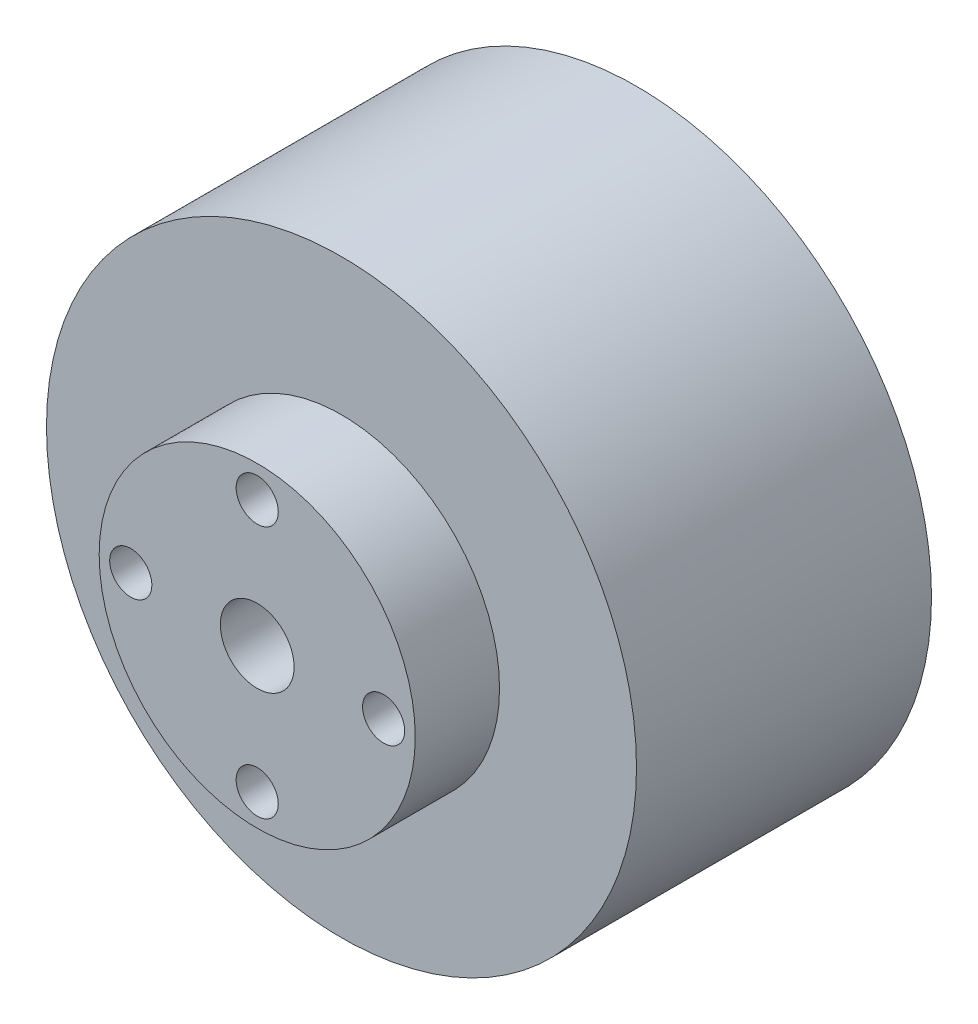
SolidWorks part; units mm, degrees
ref_plane "前视基准面" through (0, 0, 0) normal (0, 0, 1) x (1, 0, 0)
ref_plane "上视基准面" through (0, 0, 0) normal (0, 1, 0) x (1, 0, 0)
ref_plane "右视基准面" through (0, 0, 0) normal (1, 0, 0) x (0, 0, -1)
sketch "草图1" plane through (0, 0, 0) normal (0, 0, 1) x (1, 0, 0)
  circle A0 centre (0, 0) radius 14
  dimension "D1" = 28
extrude "凸台-拉伸1" add sketch "草图1" along normal blind 14
sketch "草图3" plane through (0, 0, 14) normal (0, 0, 1) x (1, 0, 0)
  circle A0 centre (0, 0) radius 7.5
  dimension "D1" = 15
extrude "凸台-拉伸3" add sketch "草图3" along normal blind 4
sketch "草图4" plane through (0, 0, 18) normal (0, 0, 1) x (1, 0, 0)
  circle A0 centre (0, 0) radius 1.75
  dimension "D1" = 3.5
extrude "切除-拉伸1" cut sketch "草图4" against normal through all
sketch "草图5" plane through (0, 0, 18) normal (0, 0, 1) x (1, 0, 0)
  line L0 (-17.4028, 0) -> (19.2585, 0) construction
  line L1 (0, 18.129) -> (0, -19.9613) construction
  circle A0 centre (0, -6) radius 1
  circle A1 centre (-6, 0) radius 1
  circle A2 centre (0, 6) radius 1
  circle A3 centre (6, 0) radius 1
  dimension "D1" = 2
  dimension "D2" = 6
  dimension "D3" = 6
  dimension "D4" = 6
  dimension "D5" = 6
extrude "切除-拉伸2" cut sketch "草图5" against normal blind 3 contours A3 | A1 | A0 | A2
sketch "草图6" plane through (0, 0, 0) normal (0, 0, 1) x (1, 0, 0)
  line L0 (24.9097, 0) -> (-28.6773, 0) construction
  line L1 (0, 19.7976) -> (0, -23.3744) construction
  circle A0 centre (0, 8) radius 1.5
  circle A1 centre (-8, 0) radius 1.5
  circle A2 centre (0, -8) radius 1.5
  circle A3 centre (8, 0) radius 1.5
  dimension "D1" = 3
  dimension "D2" = 8
  dimension "D3" = 8
  dimension "D4" = 8
  dimension "D5" = 8
extrude "切除-拉伸3" cut sketch "草图6" along normal blind 3
